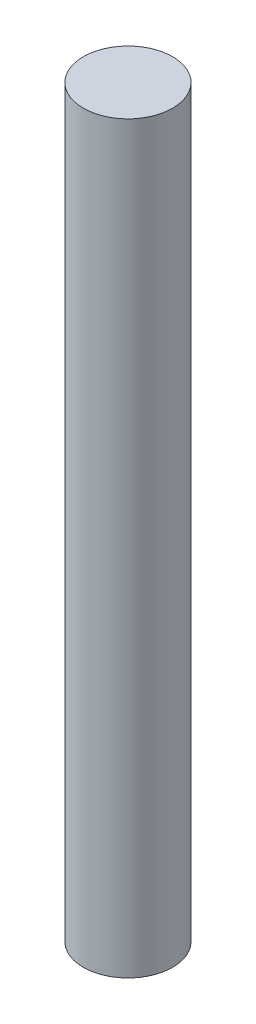
SolidWorks part; units mm, degrees
material "6061 Alloy"
ref_plane "Front Plane" through (0, 0, 0) normal (0, 0, 1) x (1, 0, 0)
ref_plane "Top Plane" through (0, 0, 0) normal (0, 1, 0) x (1, 0, 0)
ref_plane "Right Plane" through (0, 0, 0) normal (1, 0, 0) x (0, 0, -1)
sketch "Sketch1" plane through (0, 0, 0) normal (0, 1, 0) x (1, 0, 0)
  circle A0 centre (0, 0) radius 1.524
  dimension "D1" = 3.048
extrude "Boss-Extrude1" add sketch "Sketch1" along normal blind 25.4
